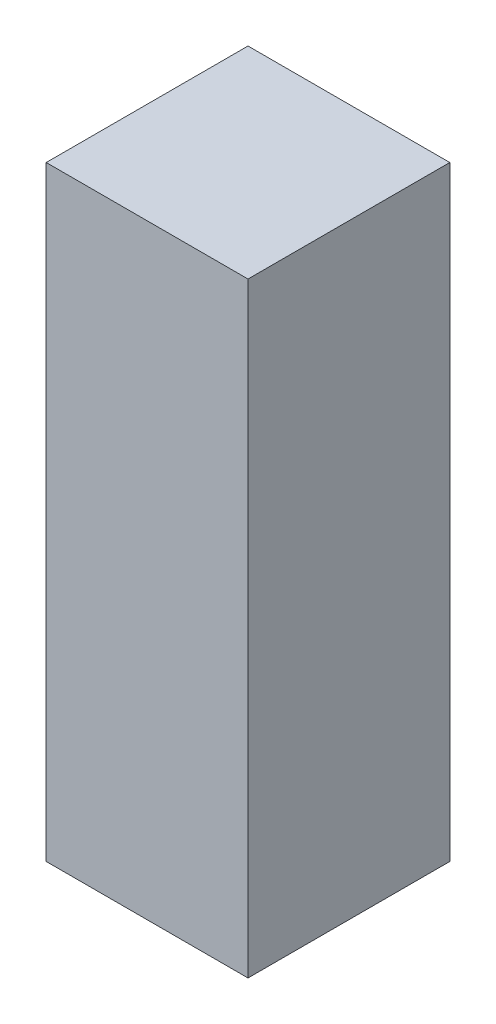
SolidWorks part; units mm, degrees
ref_plane "Front Plane" through (0, 0, 0) normal (0, 0, 1) x (1, 0, 0)
ref_plane "Top Plane" through (0, 0, 0) normal (0, 1, 0) x (1, 0, 0)
ref_plane "Right Plane" through (0, 0, 0) normal (1, 0, 0) x (0, 0, -1)
sketch "Sketch1" plane through (0, 0, 0) normal (0, 1, 0) x (1, 0, 0)
  line L1 (37.5, -37.5) -> (-37.5, -37.5)
  line L2 (37.5, -37.5) -> (37.5, 37.5)
  line L3 (37.5, 37.5) -> (-37.5, 37.5)
  line L4 (-37.5, -37.5) -> (-37.5, 37.5)
  line L5 (37.5, -37.5) -> (-37.5, 37.5) construction
  line L6 (37.5, 37.5) -> (-37.5, -37.5) construction
  point P0 (0, 0)
  dimension "D1" = 75
  dimension "D2" = 75
extrude "Boss-Extrude1" add sketch "Sketch1" along normal blind 225
equation "\"D2@Sketch1\"=\"D1@Sketch1\""
